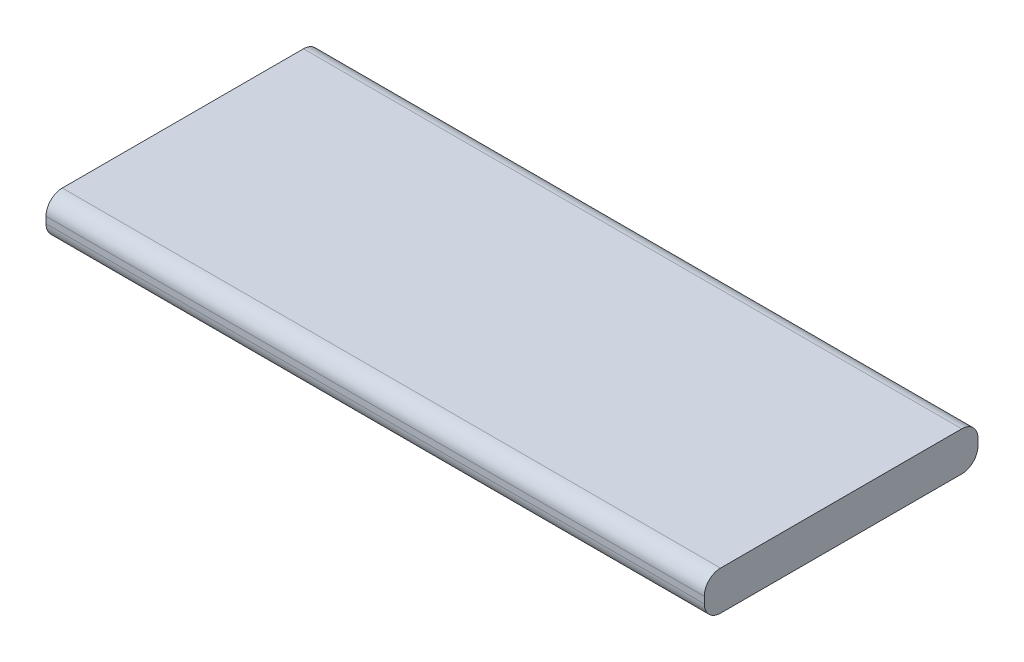
SolidWorks part; units mm, degrees
ref_plane "Front Plane" through (0, 0, 0) normal (0, 0, 1) x (1, 0, 0)
ref_plane "Top Plane" through (0, 0, 0) normal (0, 1, 0) x (1, 0, 0)
ref_plane "Right Plane" through (0, 0, 0) normal (1, 0, 0) x (0, 0, -1)
sketch "Sketch1" plane through (0, 0, 0) normal (0, 1, 0) x (1, 0, 0)
  line L1 (5.05, -2.1) -> (-5.05, -2.1)
  line L2 (5.05, -2.1) -> (5.05, 2.1)
  line L3 (5.05, 2.1) -> (-5.05, 2.1)
  line L4 (-5.05, -2.1) -> (-5.05, 2.1)
  line L5 (5.05, -2.1) -> (-5.05, 2.1) construction
  line L6 (5.05, 2.1) -> (-5.05, -2.1) construction
  point P0 (0, 0)
  dimension "D1" = 10.1
  dimension "D2" = 4.2
extrude "Boss-Extrude1" add sketch "Sketch1" along normal blind 0.6
fillet "Fillet1" radius 0.25 2 edges at (0, 0.6, -2.1) (0, 0.6, 2.1)
fillet "Fillet2" radius 0.25 2 edges at (0, 0, 2.1) (0, 0, -2.1)
